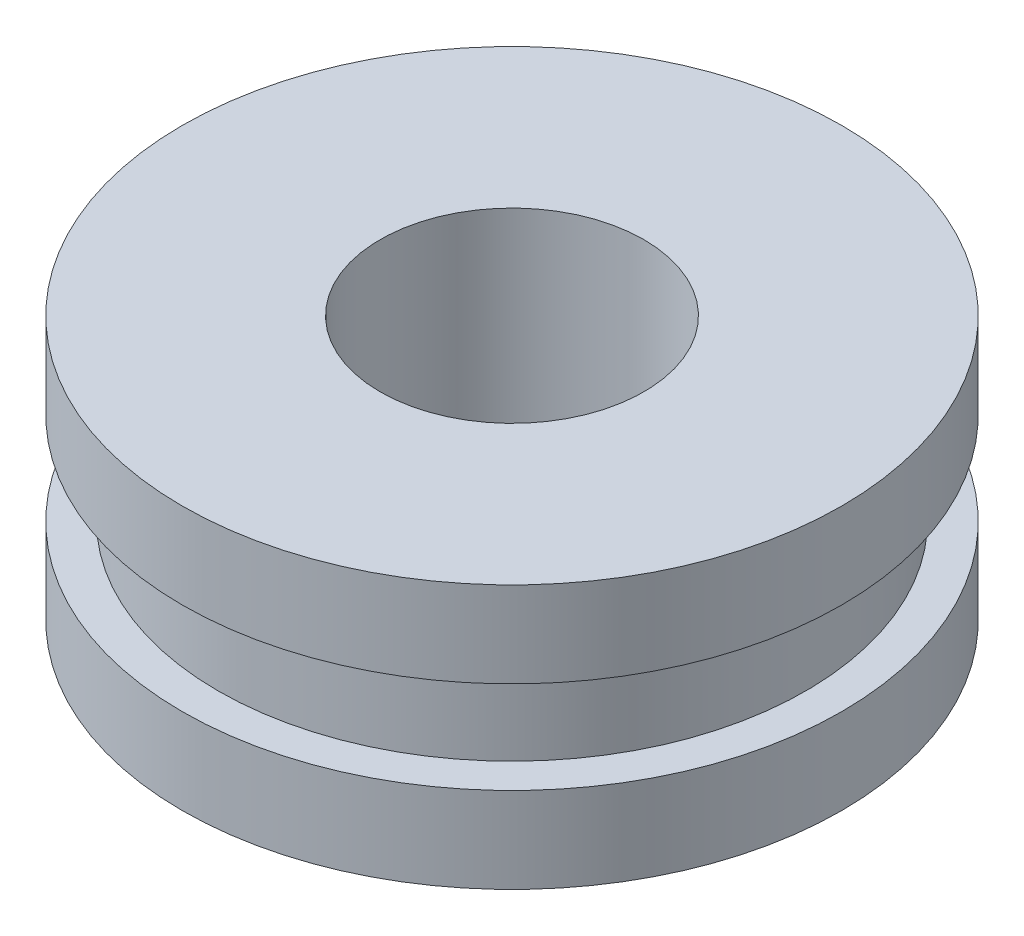
SolidWorks part; units mm, degrees
ref_plane "Front Plane" through (0, 0, 0) normal (0, 0, 1) x (1, 0, 0)
ref_plane "Top Plane" through (0, 0, 0) normal (0, 1, 0) x (1, 0, 0)
ref_plane "Right Plane" through (0, 0, 0) normal (1, 0, 0) x (0, 0, -1)
sketch "Sketch1" plane through (0, 0, 0) normal (0, 1, 0) x (1, 0, 0)
  circle A0 centre (0, 0) radius 2
  circle A1 centre (0, 0) radius 5
  dimension "D1" = 10
  dimension "D2" = 4
extrude "Boss-Extrude1" add sketch "Sketch1" along normal blind 1.3
sketch "Sketch2" plane through (0, 1.3, 0) normal (0, 1, 0) x (1, 0, 0)
  circle A0 centre (0, 0) radius 2 construction
  circle A1 centre (0, 0) radius 2
  circle A2 centre (0, 0) radius 4.4563
extrude "Boss-Extrude2" add sketch "Sketch2" along normal blind 1.4
pattern_linear "LPattern2" count 2 spacing 2.7 along (0, 1, 0) of "Boss-Extrude1"
